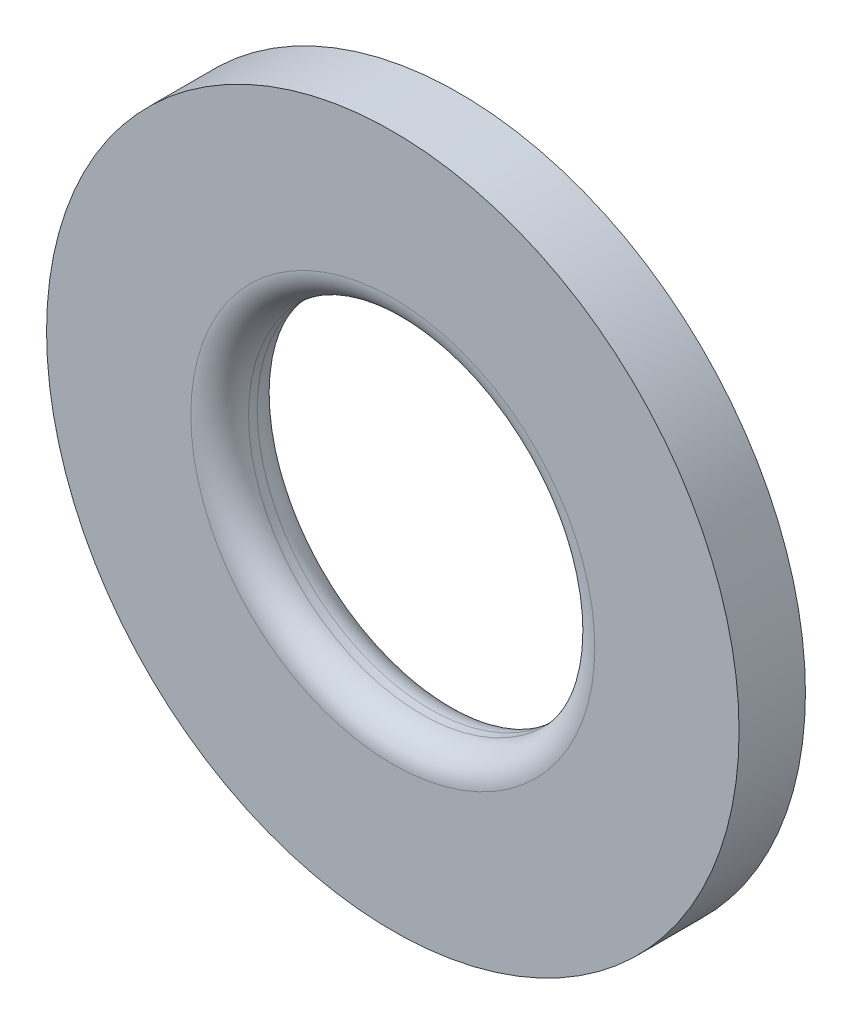
SolidWorks part; units mm, degrees
ref_plane "前视基准面" through (0, 0, 0) normal (0, 0, 1) x (1, 0, 0)
ref_plane "上视基准面" through (0, 0, 0) normal (0, 1, 0) x (1, 0, 0)
ref_plane "右视基准面" through (0, 0, 0) normal (1, 0, 0) x (0, 0, -1)
sketch "草图1" plane through (0, 0, 0) normal (0, 0, 1) x (1, 0, 0)
  circle A0 centre (0, 0) radius 12
  circle A1 centre (0, 0) radius 6
  dimension "D1" = 24
  dimension "D2" = 12
extrude "凸台-拉伸1" add sketch "草图1" along normal blind 2.3
fillet "圆角1" radius 1 2 edges at (6, 0, 0) (6, 0, 2.3)
